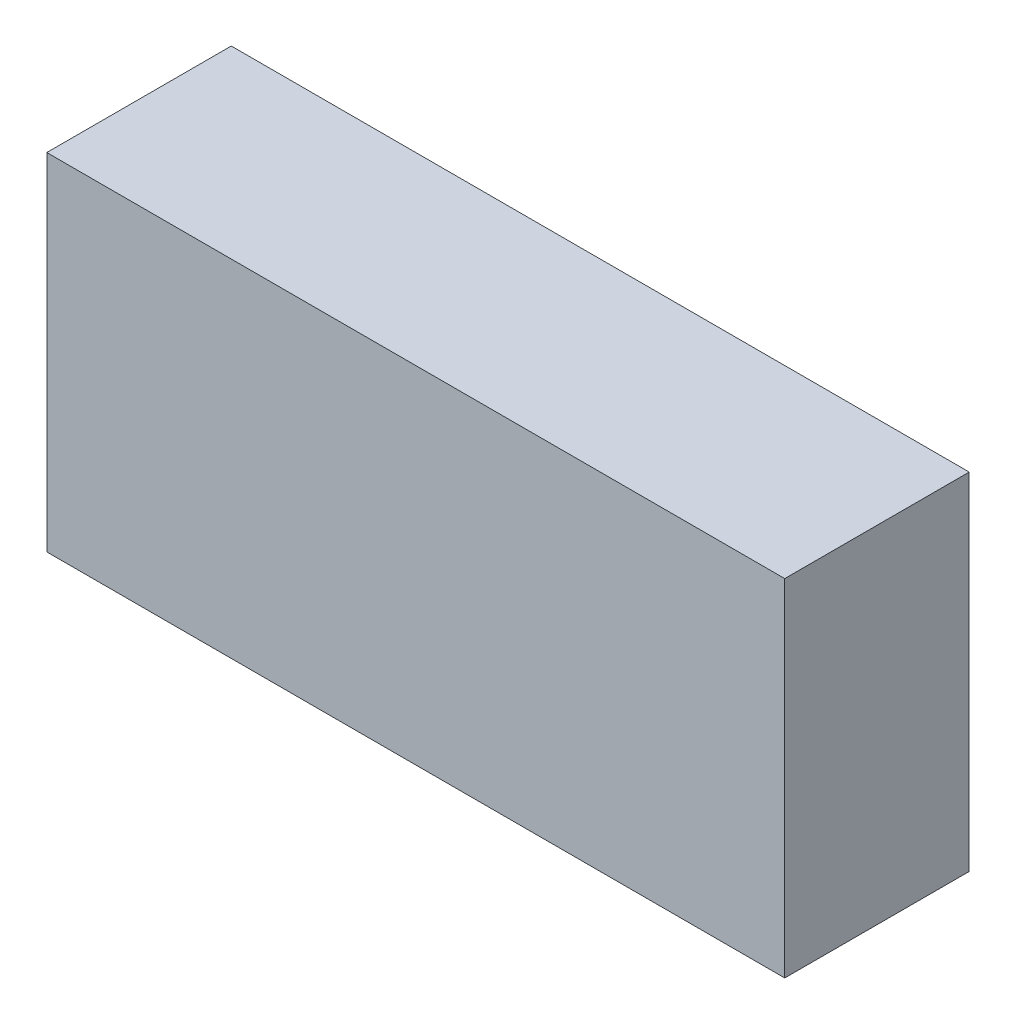
SolidWorks part; units mm, degrees
ref_plane "前视基准面" through (0, 0, 0) normal (0, 0, 1) x (1, 0, 0)
ref_plane "上视基准面" through (0, 0, 0) normal (0, 1, 0) x (1, 0, 0)
ref_plane "右视基准面" through (0, 0, 0) normal (1, 0, 0) x (0, 0, -1)
sketch "草图1" plane through (0, 0, 0) normal (0, 0, 1) x (1, 0, 0)
  line L1 (32, -15) -> (-32, -15)
  line L2 (32, -15) -> (32, 15)
  line L3 (32, 15) -> (-32, 15)
  line L4 (-32, -15) -> (-32, 15)
  line L5 (32, -15) -> (-32, 15) construction
  line L6 (32, 15) -> (-32, -15) construction
  point P0 (0, 0)
  dimension "D1" = 64
  dimension "D2" = 30
extrude "凸台-拉伸1" add sketch "草图1" against normal blind 16
